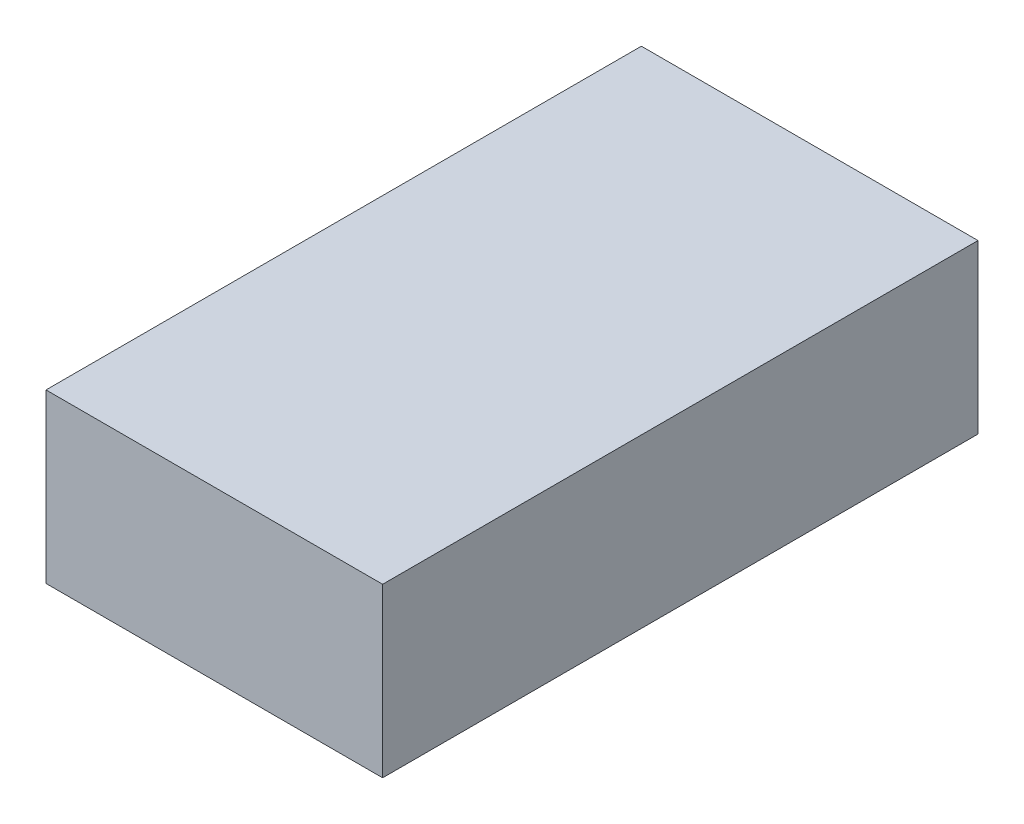
SolidWorks part; units mm, degrees
ref_plane "Plan de face" through (0, 0, 0) normal (0, 0, 1) x (1, 0, 0)
ref_plane "Plan de dessus" through (0, 0, 0) normal (0, 1, 0) x (1, 0, 0)
ref_plane "Plan de droite" through (0, 0, 0) normal (1, 0, 0) x (0, 0, -1)
ref_plane "Fuselage_sections_A-F" through (0, 0, -25) normal (0, 0, 1) x (1, 0, 0)
ref_plane "Fuselage_sections_G-L" through (0, 0, -535) normal (0, 0, 1) x (1, 0, 0)
sketch "Front_view" plane through (0, 0, 0) normal (0, 0, 1) x (1, 0, 0)
  line L0 (-210.6667, 61) -> (226.6667, 61) construction
  line L1 (0, -457.7554) -> (0, 457.7554) construction
  line L2 (-609.4687, 0) -> (609.4687, 0) construction
  point P6 (0, 0)
  point P10 (0, 0)
sketch "Right_view" plane through (0, 0, 0) normal (1, 0, 0) x (0, 0, -1)
  line L0 (121.8333, 89.5) -> (773.1667, 89.5) construction
  line L1 (122.8333, 88.5) -> (774.1667, 88.5) construction
sketch "Top_view" plane through (0, 0, 0) normal (0, 1, 0) x (1, 0, 0)
  line L0 (-200.6667, 273) -> (228.6667, 273) construction
  line L1 (-320.884, 536.2025) -> (320.884, 536.2025) construction
  point P5 (0, 536.2025)
sketch "Sections_A-F" plane through (0, 0, -25) normal (0, 0, 1) x (1, 0, 0)
  line L0 (256, 506.5) -> (1280, 506.5) construction
  line L1 (-93.8333, -12) -> (42.8333, -12) construction
  line L2 (-433.6046, 0) -> (433.6046, 0) construction
  line L4 (0, -377.9081) -> (0, 377.9081) construction
  point P7 (0, 0)
  point P11 (0, 0)
sketch "Sections_G-L" plane through (0, 0, -535) normal (0, 0, 1) x (1, 0, 0)
  line L0 (-41.1667, 2.5) -> (94.1667, 2.5) construction
  line L1 (-320.884, 0) -> (320.884, 0) construction
  line L2 (-320.884, 0) -> (320.884, 0) construction
  line L3 (0, -400.0288) -> (0, 400.0288) construction
  point P7 (0, 0)
  point P11 (0, 0)
sketch "Sketch2" plane through (0, 0, 0) normal (0, 0, 1) x (1, 0, 0)
  line L0 (0, -457.7554) -> (0, 457.7554) construction
  line L1 (0, 91.9289) -> (303.0555, 91.9289)
  line L2 (0, 91.9289) -> (0, -58.9753)
  line L3 (0, -58.9753) -> (303.0555, -58.9753)
  line L4 (303.0555, 91.9289) -> (303.0555, -58.9753)
extrude "Boss-Extrude1" add sketch "Sketch2" against normal blind 536
ref_plane "A" through (0, 0, -38) normal (0, 0, 1) x (1, 0, 0)
ref_plane "B" through (0, 0, -45.5) normal (0, 0, 1) x (1, 0, 0)
ref_plane "C" through (0, 0, -90) normal (0, 0, 1) x (1, 0, 0)
ref_plane "D" through (0, 0, -121) normal (0, 0, 1) x (1, 0, 0)
ref_plane "D1" through (0, 0, -130) normal (0, 0, 1) x (1, 0, 0)
ref_plane "E" through (0, 0, -166.5) normal (0, 0, 1) x (1, 0, 0)
ref_plane "F" through (0, 0, -193) normal (0, 0, 1) x (1, 0, 0)
ref_plane "F1" through (0, 0, -199) normal (0, 0, 1) x (1, 0, 0)
ref_plane "G" through (0, 0, -242) normal (0, 0, 1) x (1, 0, 0)
ref_plane "G1" through (0, 0, -309) normal (0, 0, 1) x (1, 0, 0)
ref_plane "H" through (0, 0, -316) normal (0, 0, 1) x (1, 0, 0)
ref_plane "J" through (0, 0, -392) normal (0, 0, 1) x (1, 0, 0)
ref_plane "J1" through (0, 0, -418) normal (0, 0, 1) x (1, 0, 0)
ref_plane "K" through (0, 0, -468) normal (0, 0, 1) x (1, 0, 0)
ref_plane "L" through (0, 0, -498) normal (0, 0, 1) x (1, 0, 0)
